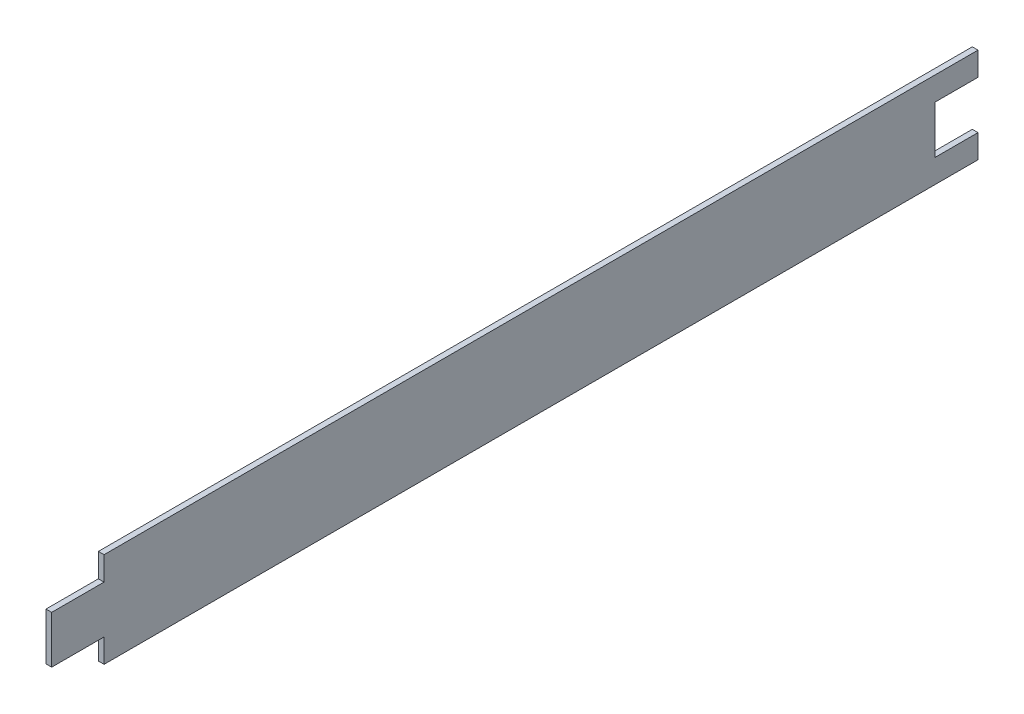
SolidWorks part; units mm, degrees
ref_plane "Plan de face" through (0, 0, 0) normal (0, 0, 1) x (1, 0, 0)
ref_plane "Plan de dessus" through (0, 0, 0) normal (0, 1, 0) x (1, 0, 0)
ref_plane "Plan de droite" through (0, 0, 0) normal (1, 0, 0) x (0, 0, -1)
sketch "Esquisse2" plane through (0, 0, 0) normal (1, 0, 0) x (0, 0, -1)
  line L1 (-230, 25) -> (230, 25)
  line L2 (-230, 25) -> (-230, -25)
  line L3 (-230, -25) -> (230, -25)
  line L4 (230, 25) -> (230, -25)
  line L5 (-230, 25) -> (230, -25) construction
  line L6 (-230, -25) -> (230, 25) construction
  line L7 (207.3515, 12.6) -> (230, 12.6)
  line L8 (-257.5694, -12.5) -> (-230, -12.5)
  line L9 (-257.5694, -12.5) -> (-257.5694, 12.5)
  line L10 (-257.5694, 12.5) -> (-230, 12.5)
  line L11 (-230, -12.5) -> (-230, 12.5)
  line L12 (207.3515, 12.6) -> (207.3515, -12.6)
  line L13 (207.3515, -12.6) -> (230, -12.6)
  line L14 (230, 12.6) -> (230, -12.6)
  point P0 (0, 0)
  point P10 (0, 0)
  point P15 (0, 0)
  point P16 (0, 0)
  dimension "D1" = 460
  dimension "D2" = 50
  dimension "D3" = 12.5
  dimension "D4" = 12.5
  dimension "D5" = 12.4
  dimension "D6" = 12.4
extrude "Boss.-Extru.3" add sketch "Esquisse2" along normal blind 3 contours L10 L9 L8 L2 | L13 L12 L7 L4 L1 L2 L3
